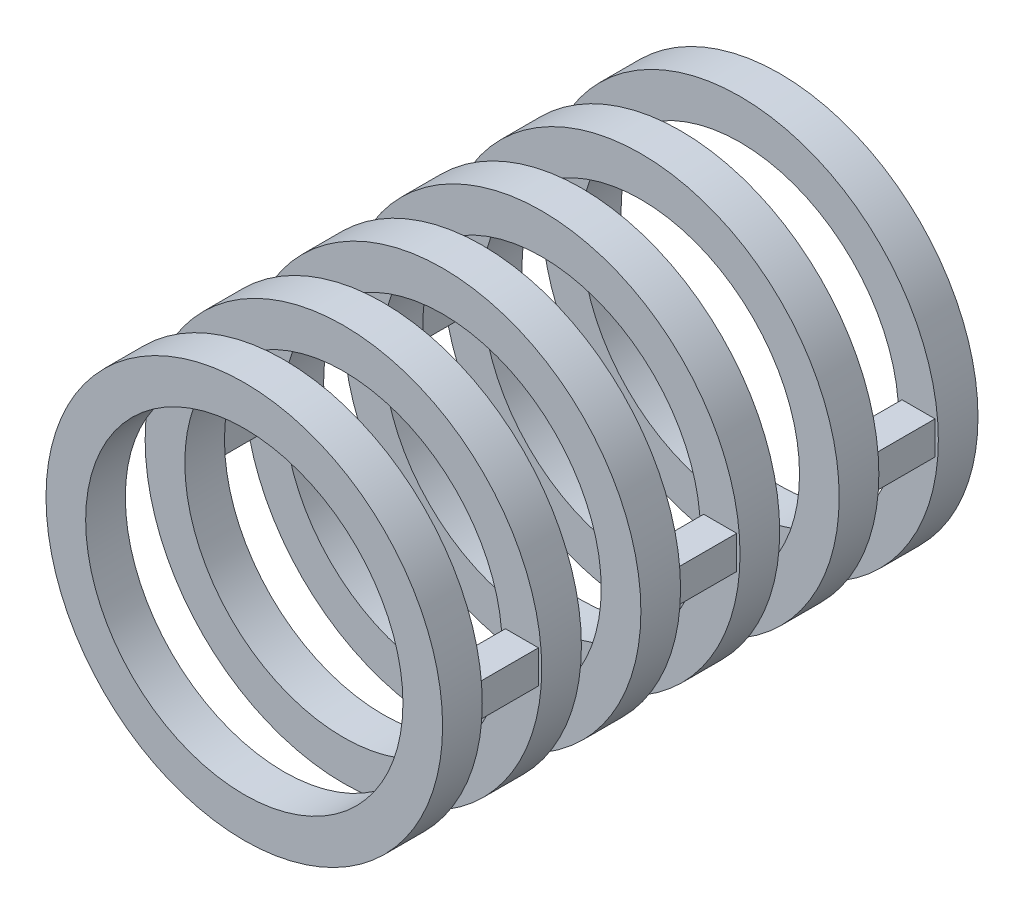
SolidWorks part; units mm, degrees
ref_plane "Front Plane" through (0, 0, 0) normal (0, 0, 1) x (1, 0, 0)
ref_plane "Top Plane" through (0, 0, 0) normal (0, 1, 0) x (1, 0, 0)
ref_plane "Right Plane" through (0, 0, 0) normal (1, 0, 0) x (0, 0, -1)
sketch "Sketch1" plane through (0, 0, 0) normal (0, 0, 1) x (1, 0, 0)
  circle A0 centre (0, 0) radius 6
  circle A1 centre (0, 0) radius 4.8
extrude "Coil1" add sketch "Sketch1" along normal blind 1.2
ref_plane "Plane_z3" through (0, 0, 3) normal (0, 0, 1) x (1, 0, 0)
sketch "Sketch2" plane through (0, 0, 3) normal (0, 0, 1) x (1, 0, 0)
  circle A0 centre (0, 0) radius 6
  circle A1 centre (0, 0) radius 4.8
extrude "Coil2" add sketch "Sketch2" along normal blind 1.2
ref_plane "Plane_z6" through (0, 0, 6) normal (0, 0, 1) x (1, 0, 0)
sketch "Sketch3" plane through (0, 0, 6) normal (0, 0, 1) x (1, 0, 0)
  circle A0 centre (0, 0) radius 6
  circle A1 centre (0, 0) radius 4.8
extrude "Coil3" add sketch "Sketch3" along normal blind 1.2
ref_plane "Plane_z9" through (0, 0, 9) normal (0, 0, 1) x (1, 0, 0)
sketch "Sketch4" plane through (0, 0, 9) normal (0, 0, 1) x (1, 0, 0)
  circle A0 centre (0, 0) radius 6
  circle A1 centre (0, 0) radius 4.8
extrude "Coil4" add sketch "Sketch4" along normal blind 1.2
ref_plane "Plane_z12" through (0, 0, 12) normal (0, 0, 1) x (1, 0, 0)
sketch "Sketch5" plane through (0, 0, 12) normal (0, 0, 1) x (1, 0, 0)
  circle A0 centre (0, 0) radius 6
  circle A1 centre (0, 0) radius 4.8
extrude "Coil5" add sketch "Sketch5" along normal blind 1.2
ref_plane "Plane_z15" through (0, 0, 15) normal (0, 0, 1) x (1, 0, 0)
sketch "Sketch6" plane through (0, 0, 15) normal (0, 0, 1) x (1, 0, 0)
  circle A0 centre (0, 0) radius 6
  circle A1 centre (0, 0) radius 4.8
extrude "Coil6" add sketch "Sketch6" along normal blind 1.2
ref_plane "Plane_z1_2" through (0, 0, 1.2) normal (0, 0, 1) x (1, 0, 0)
sketch "Sketch7" plane through (0, 0, 1.2) normal (0, 0, 1) x (1, 0, 0)
  line L0 (4.9, -0.5) -> (5.9, -0.5)
  line L1 (5.9, -0.5) -> (5.9, 0.5)
  line L2 (5.9, 0.5) -> (4.9, 0.5)
  line L3 (4.9, 0.5) -> (4.9, -0.5)
extrude "Link1" add sketch "Sketch7" along normal blind 1.8
ref_plane "Plane_z4_2" through (0, 0, 4.2) normal (0, 0, 1) x (1, 0, 0)
sketch "Sketch8" plane through (0, 0, 4.2) normal (0, 0, 1) x (1, 0, 0)
  line L0 (-4.9, 0.5) -> (-5.9, 0.5)
  line L1 (-5.9, 0.5) -> (-5.9, -0.5)
  line L2 (-5.9, -0.5) -> (-4.9, -0.5)
  line L3 (-4.9, -0.5) -> (-4.9, 0.5)
extrude "Link2" add sketch "Sketch8" along normal blind 1.8
ref_plane "Plane_z7_2" through (0, 0, 7.2) normal (0, 0, 1) x (1, 0, 0)
sketch "Sketch9" plane through (0, 0, 7.2) normal (0, 0, 1) x (1, 0, 0)
  line L0 (4.9, -0.5) -> (5.9, -0.5)
  line L1 (5.9, -0.5) -> (5.9, 0.5)
  line L2 (5.9, 0.5) -> (4.9, 0.5)
  line L3 (4.9, 0.5) -> (4.9, -0.5)
extrude "Link3" add sketch "Sketch9" along normal blind 1.8
ref_plane "Plane_z10_2" through (0, 0, 10.2) normal (0, 0, 1) x (1, 0, 0)
sketch "Sketch10" plane through (0, 0, 10.2) normal (0, 0, 1) x (1, 0, 0)
  line L0 (-4.9, 0.5) -> (-5.9, 0.5)
  line L1 (-5.9, 0.5) -> (-5.9, -0.5)
  line L2 (-5.9, -0.5) -> (-4.9, -0.5)
  line L3 (-4.9, -0.5) -> (-4.9, 0.5)
extrude "Link4" add sketch "Sketch10" along normal blind 1.8
ref_plane "Plane_z13_2" through (0, 0, 13.2) normal (0, 0, 1) x (1, 0, 0)
sketch "Sketch11" plane through (0, 0, 13.2) normal (0, 0, 1) x (1, 0, 0)
  line L0 (4.9, -0.5) -> (5.9, -0.5)
  line L1 (5.9, -0.5) -> (5.9, 0.5)
  line L2 (5.9, 0.5) -> (4.9, 0.5)
  line L3 (4.9, 0.5) -> (4.9, -0.5)
extrude "Link5" add sketch "Sketch11" along normal blind 1.8
